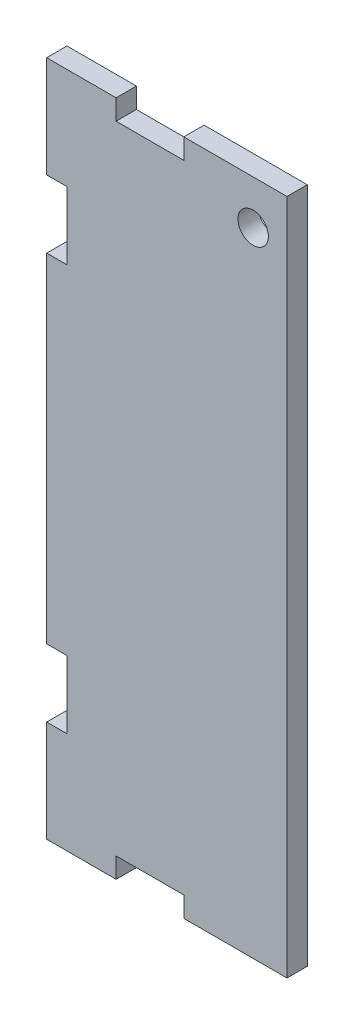
SolidWorks part; units mm, degrees
ref_plane "Front Plane" through (0, 0, 0) normal (0, 0, 1) x (1, 0, 0)
ref_plane "Top Plane" through (0, 0, 0) normal (0, 1, 0) x (1, 0, 0)
ref_plane "Right Plane" through (0, 0, 0) normal (1, 0, 0) x (0, 0, -1)
sketch "Sketch1" plane through (0, 0, 0) normal (0, 0, 1) x (1, 0, 0)
  line L0 (-15.25, 35) -> (-12.25, 35)
  line L1 (-15.25, 50) -> (15.25, 50)
  line L2 (-15.25, 50) -> (-15.25, -50)
  line L3 (-15.25, -50) -> (15.25, -50)
  line L4 (15.25, 50) -> (15.25, -50)
  line L5 (-15.25, 50) -> (15.25, -50) construction
  line L6 (-15.25, -50) -> (15.25, 50) construction
  line L7 (-12.25, 35) -> (-12.25, 25)
  line L8 (-12.25, 25) -> (-15.25, 25)
  line L9 (-15.25, 25) -> (-15.25, 35)
  line L10 (-15.25, -25) -> (-12.25, -25)
  line L11 (-12.25, -25) -> (-12.25, -35)
  line L12 (-12.25, -35) -> (-15.25, -35)
  line L13 (-15.25, -35) -> (-15.25, -25)
  line L14 (-12.25, -30) -> (-12.25, -50) construction
  line L15 (-12.25, 30) -> (-12.25, 50) construction
  line L16 (-5, 50) -> (-5, 47)
  line L17 (-5, 47) -> (5, 47)
  line L18 (5, 47) -> (5, 50)
  line L19 (0, 47) -> (0, 50) construction
  line L20 (-5, -50) -> (-5, -47)
  line L21 (-5, -47) -> (5, -47)
  line L22 (5, -47) -> (5, -50)
  line L23 (0, -47) -> (0, -50) construction
  point P0 (0, 0)
  point P20 (0, 47)
  dimension "D1" = 30.5
  dimension "D2" = 100
  dimension "D3" = 20
  dimension "D4" = 20
  dimension "D5" = 10
  dimension "D6" = 3
extrude "Boss-Extrude1" add sketch "Sketch1" along normal blind 3 contours L11 L12 L2 L3 L4 L1 L0 L7 L8 L10
sketch "Sketch2" plane through (0, 0, 0) normal (0, 0, 1) x (1, 0, 0)
  line L0 (15.25, -50) -> (20.25, -50)
  line L1 (20.25, -50) -> (20.25, 50)
  line L2 (20.25, 50) -> (15.25, 50)
  line L3 (15.25, -50) -> (15.25, 50)
  dimension "D1" = 5
extrude "Boss-Extrude2" add sketch "Sketch2" along normal blind 3
sketch "Sketch3" plane through (0, 0, 3) normal (0, 0, 1) x (1, 0, 0)
  line L0 (15.25, 50) -> (15.25, -50) construction
  line L1 (-15.25, 50) -> (-5, 50) construction
  line L2 (-15.25, -50) -> (-5, -50) construction
  line L3 (20.25, -50) -> (20.25, 50) construction
  circle A0 centre (15.25, 43.5) radius 2.25
  dimension "D2" = 4.5
  dimension "D1" = 5
  dimension "D3" = 6.5
extrude "Cut-Extrude1" cut sketch "Sketch3" against normal blind 3
